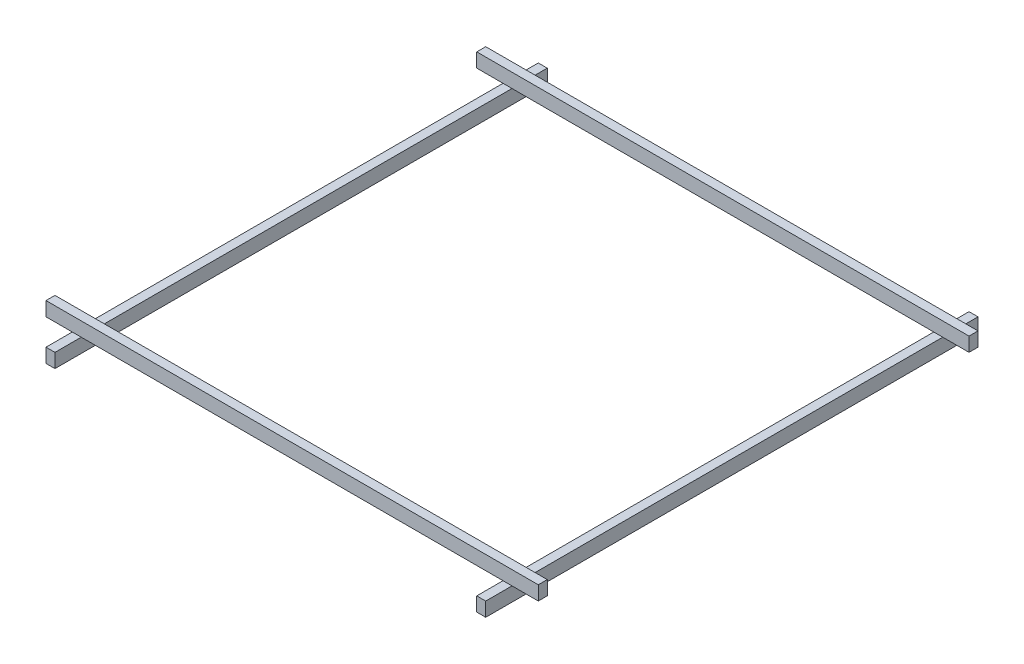
SolidWorks part; units mm, degrees
material "Doug Fir"
ref_plane "Front Plane" through (0, 0, 0) normal (0, 0, 1) x (1, 0, 0)
ref_plane "Top Plane" through (0, 0, 0) normal (0, 1, 0) x (1, 0, 0)
ref_plane "Right Plane" through (0, 0, 0) normal (1, 0, 0) x (0, 0, -1)
sketch "Lower Level" plane through (0, 0, 0) normal (0, 1, 0) x (1, 0, 0)
  line L0 (0, 0) -> (0, 4876.8)
  line L1 (4267.2, 0) -> (4267.2, 4876.8)
  line L2 (0, 2438.4) -> (4267.2, 2438.4) construction
  point P7 (2133.6, 2438.4)
  dimension "D1" = 4876.8
  dimension "D2" = 2133.6
ref_plane "Plane2" through (0, 139.7, 0) normal (0, 1, 0) x (1, 0, 0)
sketch "Sketch12" plane through (0, 139.7, 0) normal (0, 1, 0) x (1, 0, 0)
  line L0 (-304.8, 4572) -> (4572, 4572)
  line L1 (4572, 304.8) -> (-304.8, 304.8)
  line L2 (2133.6, 4572) -> (2133.6, 304.8) construction
  point P0 (2133.6, 2438.4)
  point P6 (2133.6, 304.8)
  point P7 (2133.6, 4572)
  point P10 (2133.6, 2438.4)
  dimension "D1" = 4876.8
  dimension "D2" = 2133.6
other "Profiles 4X6(1)"
ref_plane "Plane1" through (0, 0, 0) normal (0, 0, -1) x (-1, 0, 0)
sketch "Sketch1" plane through (0, 0, 0) normal (0, 0, -1) x (-1, 0, 0)
  line L1 (-44.45, 69.85) -> (44.45, 69.85)
  line L2 (-44.45, 69.85) -> (-44.45, -69.85)
  line L3 (-44.45, -69.85) -> (44.45, -69.85)
  line L4 (44.45, 69.85) -> (44.45, -69.85)
  line L5 (-44.45, 69.85) -> (44.45, -69.85) construction
  line L6 (-44.45, -69.85) -> (44.45, 69.85) construction
  point P0 (0, 0)
  point P6 (0, 69.85)
  point P7 (0, -69.85)
  point P8 (44.45, 0)
  point P9 (-44.45, 0)
  point P10 (0, 0)
  dimension "D1" = 88.9
  dimension "D2" = 139.7
sketch3d "3DSketch2"
  line L0 (2133.6, 139.7, -2438.4) -> (2133.6, 0, -2438.4)
  line L1 (0, 0, -2438.4) -> (4267.2, 0, -2438.4) construction
equation "\"Width\" = 84"
equation "\"Length\"=192"
equation "\"D1@Lower Level\"=\"Length\""
equation "\"D2@Lower Level\"=\"Width\""
equation "\"D1@Sketch12\"=\"Length\""
equation "\"D2@Sketch12\"=\"Width\""
